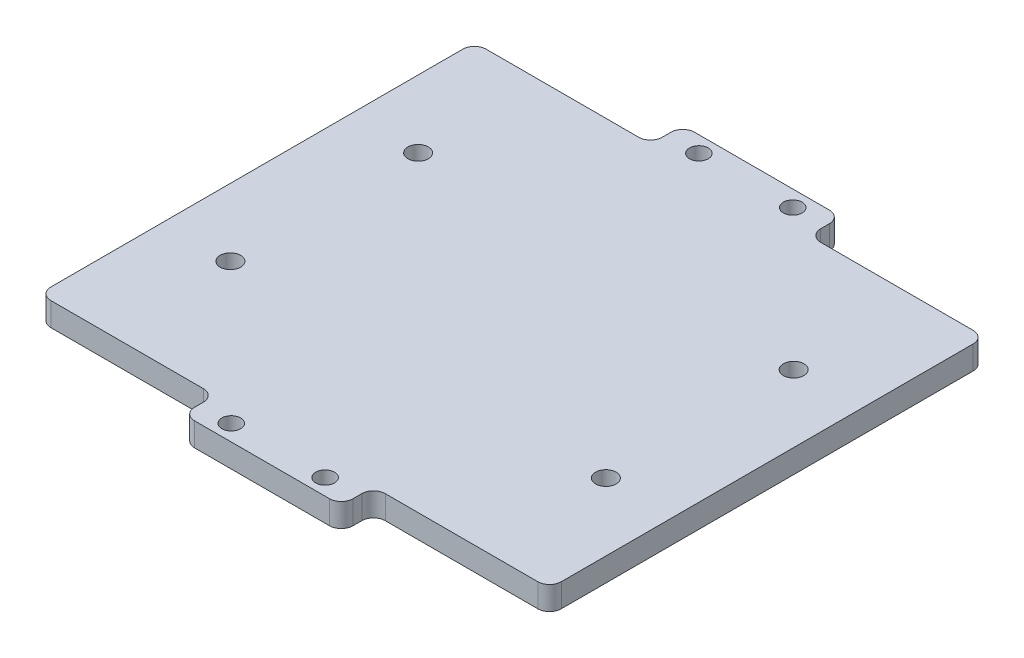
SolidWorks part; units mm, degrees
ref_plane "前视基准面" through (0, 0, 0) normal (0, 0, 1) x (1, 0, 0)
ref_plane "上视基准面" through (0, 0, 0) normal (0, 1, 0) x (1, 0, 0)
ref_plane "右视基准面" through (0, 0, 0) normal (1, 0, 0) x (0, 0, -1)
sketch "草图1" plane through (0, 0, 0) normal (0, 1, 0) x (1, 0, 0)
  line L1 (-43.5, 42.6) -> (43.5, 42.6)
  line L2 (-43.5, 42.6) -> (-43.5, -42.6)
  line L3 (-43.5, -42.6) -> (43.5, -42.6)
  line L4 (43.5, 42.6) -> (43.5, -42.6)
  line L5 (-43.5, 42.6) -> (43.5, -42.6) construction
  line L6 (-43.5, -42.6) -> (43.5, 42.6) construction
  point P0 (0, 0)
  dimension "D1" = 87
  dimension "D2" = 85.2
extrude "凸台-拉伸1" add sketch "草图1" along normal blind 4
sketch "草图2" plane through (0, 4, 0) normal (0, 1, 0) x (1, 0, 0)
  line L0 (0, 42.6) -> (0, -11.6152) construction
  line L1 (-73.5, 48.1) -> (-13.5, 48.1)
  line L2 (-73.5, 48.1) -> (-73.5, 37.1)
  line L3 (-73.5, 37.1) -> (-13.5, 37.1)
  line L4 (-13.5, 48.1) -> (-13.5, 37.1)
  line L5 (-73.5, 48.1) -> (-13.5, 37.1) construction
  line L6 (-73.5, 37.1) -> (-13.5, 48.1) construction
  line L7 (13.5, 37.1) -> (73.5, 37.1)
  line L8 (13.5, 37.1) -> (13.5, 48.1)
  line L9 (13.5, 48.1) -> (73.5, 48.1)
  line L10 (73.5, 37.1) -> (73.5, 48.1)
  line L11 (13.5, 37.1) -> (73.5, 48.1) construction
  line L12 (13.5, 48.1) -> (73.5, 37.1) construction
  line L13 (43.5, 42.6) -> (-43.5, 42.6) construction
  line L14 (-43.5, 0) -> (48.5635, 0) construction
  line L15 (-43.5, 42.6) -> (-43.5, -42.6) construction
  line L16 (13.5, -37.1) -> (13.5, -48.1)
  line L17 (13.5, -37.1) -> (73.5, -37.1)
  line L18 (-73.5, -37.1) -> (-13.5, -37.1)
  line L19 (13.5, -48.1) -> (73.5, -37.1) construction
  line L20 (13.5, -37.1) -> (73.5, -48.1) construction
  line L21 (-73.5, -37.1) -> (-13.5, -48.1) construction
  line L22 (-73.5, -48.1) -> (-13.5, -37.1) construction
  line L23 (73.5, -37.1) -> (73.5, -48.1)
  line L24 (13.5, -48.1) -> (73.5, -48.1)
  line L25 (-13.5, -48.1) -> (-13.5, -37.1)
  line L26 (-73.5, -48.1) -> (-73.5, -37.1)
  line L27 (-73.5, -48.1) -> (-13.5, -48.1)
  point P0 (-43.5, 42.6)
  point P6 (43.5, 42.6)
  point P29 (43.5, -42.6)
  point P30 (-43.5, -42.6)
  dimension "D1" = 13.5
  dimension "D2" = 13.5
  dimension "D3" = 11
extrude "切除-拉伸1" cut sketch "草图2" against normal blind 4
sketch "草图3" plane through (0, 4, 0) normal (0, 1, 0) x (1, 0, 0)
  line L2 (-13.5, -37.1) -> (-43.5, -37.1) construction
  line L3 (-43.5, 37.1) -> (-13.5, 37.1) construction
  line L5 (-32, 16) -> (32, -16) construction
  line L6 (-32, -16) -> (32, 16) construction
  circle A0 centre (-32, 16) radius 1.75
  circle A1 centre (32, 16) radius 1.75
  circle A2 centre (-32, -16) radius 1.75
  circle A3 centre (32, -16) radius 1.75
  point P0 (0, 0)
  dimension "D3" = 3.5
  dimension "D5" = 21.1
  dimension "D6" = 21.1
  dimension "D1" = 64
  dimension "D2" = 32
  dimension "D4" = 32
extrude "切除-拉伸2" cut sketch "草图3" against normal blind 4
sketch "草图4" plane through (0, 4, 0) normal (0, 1, 0) x (1, 0, 0)
  line L0 (-43.5, 0) -> (43.5, 0) construction
  line L1 (-43.5, 37.1) -> (-43.5, -37.1) construction
  line L2 (43.5, -37.1) -> (43.5, 37.1) construction
  line L3 (13.5, 42.6) -> (-13.5, 42.6) construction
  line L4 (0, 42.6) -> (0, 0) construction
  circle A0 centre (-8, 39.85) radius 1.6
  circle A1 centre (8, 39.85) radius 1.6
  circle A2 centre (8, -39.85) radius 1.6
  circle A3 centre (-8, -39.85) radius 1.6
  dimension "D1" = 3.2
  dimension "D3" = 8
  dimension "D2" = 2.75
  dimension "D4" = 8
extrude "切除-拉伸3" cut sketch "草图4" against normal blind 4
fillet "圆角3" radius 2 12 edges at (43.5, 2, -37.1) (43.5, 2, 37.1) (13.5, 2, 37.1) (13.5, 2, 42.6) (-13.5, 2, 42.6) (-13.5, 2, 37.1) (-43.5, 2, 37.1) (-13.5, 2, -37.1) (-13.5, 2, -42.6) (13.5, 2, -42.6) (13.5, 2, -37.1) (-43.5, 2, -37.1)
